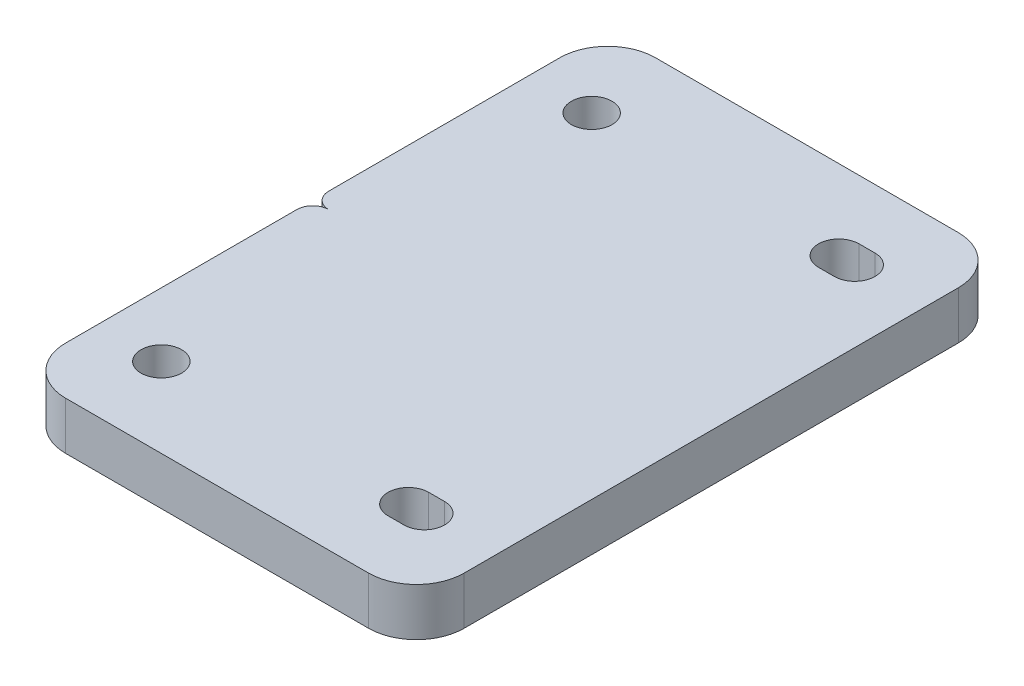
SolidWorks part; units mm, degrees
material "Клен"
ref_plane "Спереди" through (0, 0, 0) normal (0, 0, 1) x (1, 0, 0)
ref_plane "Сверху" through (0, 0, 0) normal (0, 1, 0) x (1, 0, 0)
ref_plane "Справа" through (0, 0, 0) normal (1, 0, 0) x (0, 0, -1)
sketch "Эскиз1" plane through (0, 0, 0) normal (0, 1, 0) x (1, 0, 0)
  line L0 (-41.181, -0.0464) -> (44.1026, -0.0464) construction
  line L10 (-19, -37) -> (19, -37)
  line L11 (-25, -31) -> (-25, 31)
  line L12 (-19, 37) -> (19, 37)
  line L13 (25, -31) -> (25, 31)
  line L14 (-25, -37) -> (25, 37) construction
  line L15 (-25, 37) -> (25, -37) construction
  arc A4 (19, 37) -> (25, 31) centre (19, 31) cw
  arc A5 (19, -37) -> (25, -31) centre (19, -31) ccw
  arc A6 (-19, -37) -> (-25, -31) centre (-19, -31) cw
  arc A7 (-25, 31) -> (-19, 37) centre (-19, 31) cw
  point P0 (0, 0)
  dimension "D1" = 6
  dimension "D2" = 74
  dimension "D3" = 50
extrude "Бобышка-Вытянуть1" add sketch "Эскиз1" along normal blind 6
sketch "Эскиз2" plane through (0, 0, 0) normal (0, -1, 0) x (1, 0, 0)
  line L0 (0, -37.0349) -> (0, 29.2907) construction
  line L1 (16, -27) -> (14, -27) construction
  line L2 (16, -29.55) -> (14, -29.55)
  line L3 (16, -24.45) -> (14, -24.45)
  line L6 (-46.1924, 0) -> (55.6646, 0) construction
  line L7 (16, 27) -> (14, 27) construction
  line L8 (16, 29.55) -> (14, 29.55)
  line L9 (16, 24.45) -> (14, 24.45)
  line L10 (-25, -31) -> (-25, 31) construction
  line L11 (19, -37) -> (-19, -37) construction
  circle A0 centre (-17, -27) radius 2.55
  arc A1 (16, -29.55) -> (16, -24.45) centre (16, -27) ccw
  arc A2 (14, -24.45) -> (14, -29.55) centre (14, -27) ccw
  arc A3 (16, 29.55) -> (16, 24.45) centre (16, 27) cw
  arc A4 (14, 24.45) -> (14, 29.55) centre (14, 27) cw
  circle A5 centre (-17, 27) radius 2.55
  point P7 (15, -27)
  point P12 (15, -29.55)
  point P13 (0, 0)
  point P21 (15, 27)
  point P28 (0, 0)
  point P30 (0, 29.2907)
  point P31 (0, -37.0349)
  point P34 (-9.1249, -25)
  dimension "D1" = 5.1
  dimension "D2" = 5.1
  dimension "D3" = 2
  dimension "D4" = 33
  dimension "D5" = 8
  dimension "D6" = 10
extrude "Вырез-Вытянуть1" cut sketch "Эскиз2" against normal through all
sketch "Эскиз3" plane through (0, 0, 0) normal (0, -1, 0) x (1, 0, 0)
  line L0 (-23, 0) -> (27.7687, 0) construction
  line L1 (-25, -31) -> (-25, 31) construction
  line L2 (-25, -2) -> (-25, 2)
  arc A0 (-23, 0) -> (-25, -2) centre (-23, -2) ccw
  arc A1 (-23, 0) -> (-25, 2) centre (-23, 2) cw
  point P3 (-25, -2)
  point P4 (-23, 0)
  point P7 (-25, 2)
  dimension "D2" = 2
  dimension "D1" = 2
extrude "Вырез-Вытянуть2" cut sketch "Эскиз3" against normal through all
equation "\"D2@Эскиз2\"=\"D1@Эскиз2\""
